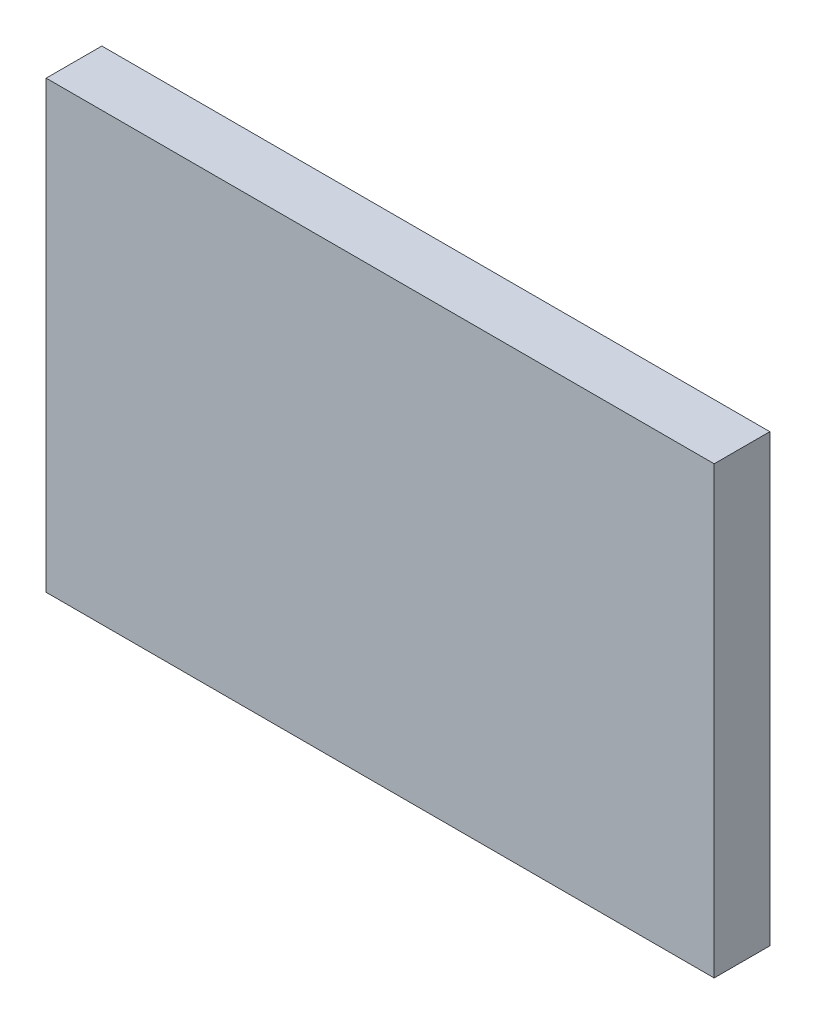
SolidWorks part; units mm, degrees
material "Pine"
ref_plane "Front Plane" through (0, 0, 0) normal (0, 0, 1) x (1, 0, 0)
ref_plane "Top Plane" through (0, 0, 0) normal (0, 1, 0) x (1, 0, 0)
ref_plane "Right Plane" through (0, 0, 0) normal (1, 0, 0) x (0, 0, -1)
sketch "Sketch1" plane through (0, 0, 0) normal (0, 0, 1) x (1, 0, 0)
  line L1 (-76.2, -50.8) -> (76.2, -50.8)
  line L2 (-76.2, -50.8) -> (-76.2, 50.8)
  line L3 (-76.2, 50.8) -> (76.2, 50.8)
  line L4 (76.2, -50.8) -> (76.2, 50.8)
  line L5 (-76.2, -50.8) -> (76.2, 50.8) construction
  line L6 (-76.2, 50.8) -> (76.2, -50.8) construction
  point P0 (0, 0)
  dimension "D1" = 152.4
  dimension "D2" = 101.6
extrude "Boss-Extrude1" add sketch "Sketch1" along normal mid plane 12.7 contours L3 L4 L1 L2
